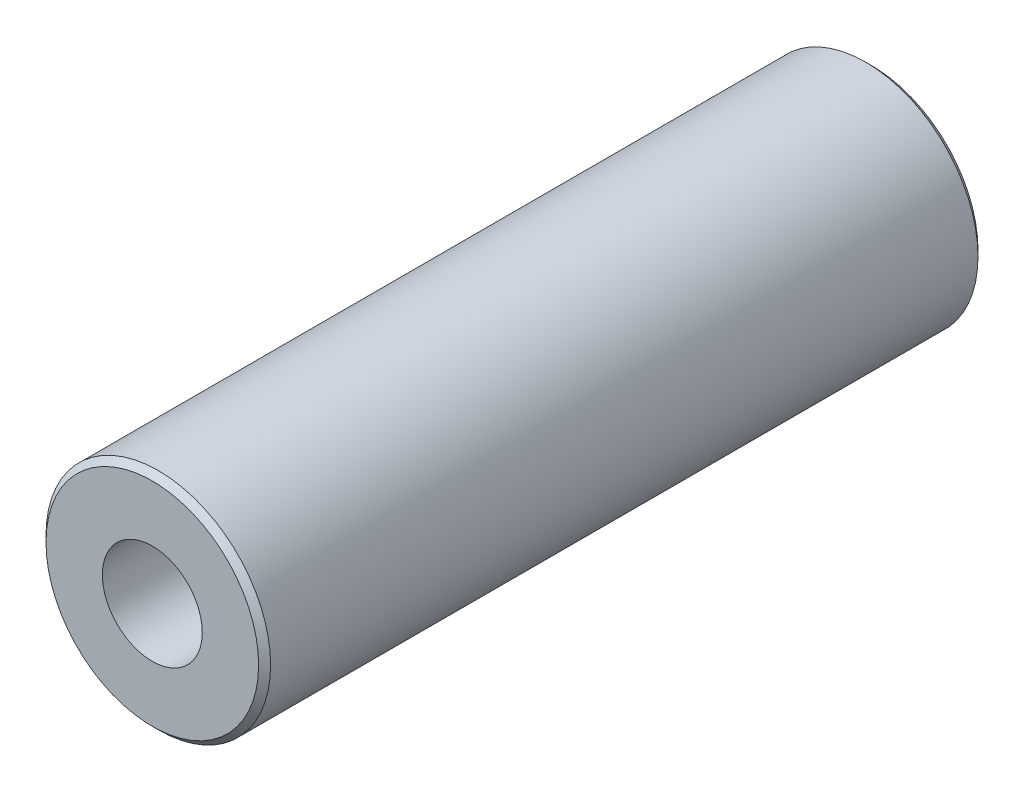
SolidWorks part; units mm, degrees
material "Alloy Steel"
ref_plane "Front" through (0, 0, 0) normal (0, 0, 1) x (1, 0, 0)
ref_plane "Top" through (0, 0, 0) normal (0, 1, 0) x (1, 0, 0)
ref_plane "Right" through (0, 0, 0) normal (1, 0, 0) x (0, 0, -1)
sketch "Sketch1" plane through (0, 0, 0) normal (0, 0, 1) x (1, 0, 0)
  circle A0 centre (0, 0) radius 7.1374
  circle A1 centre (0, 0) radius 3.175
  dimension "D1" = 14.2748
  dimension "D2" = 6.35
extrude "Boss-Extrude1" add sketch "Sketch1" along normal mid plane 45.72
chamfer "Chamfer1" distance 0.381 angle 45 2 edges at (7.1374, 0, -22.86) (7.1374, 0, 22.86)
